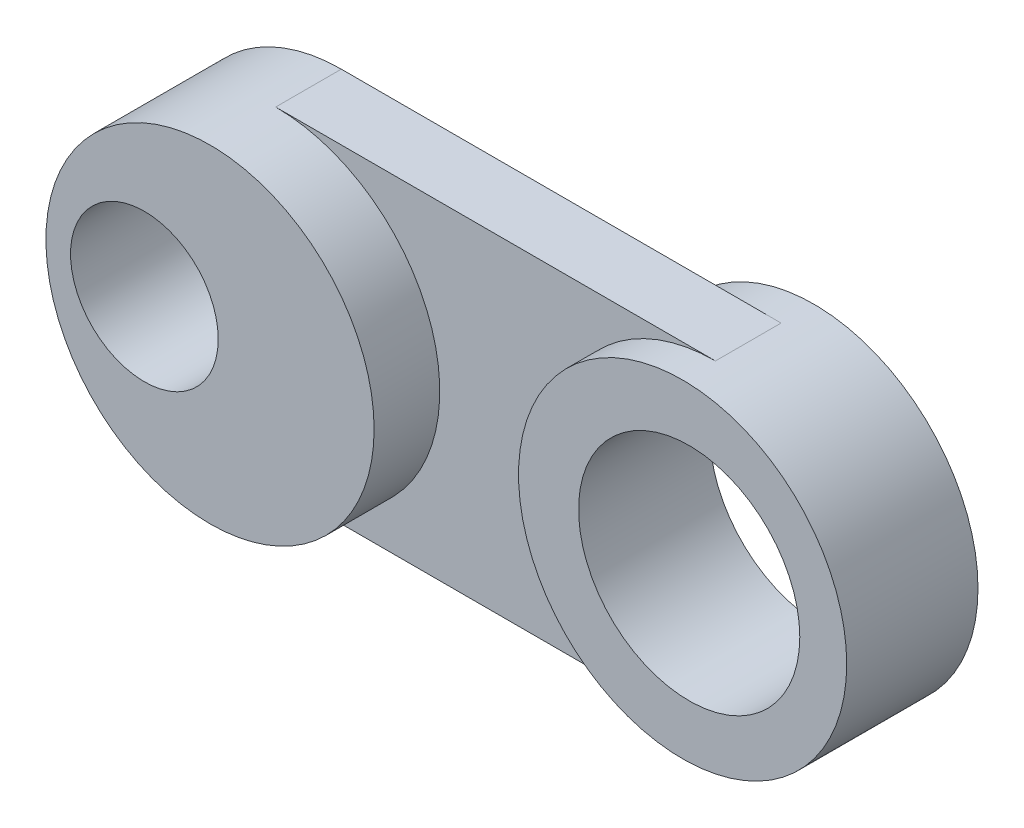
SolidWorks part; units mm, degrees
material "Custom Plastic"
ref_plane "Front Plane" through (0, 0, 0) normal (0, 0, 1) x (1, 0, 0)
ref_plane "Top Plane" through (0, 0, 0) normal (0, 1, 0) x (1, 0, 0)
ref_plane "Right Plane" through (0, 0, 0) normal (1, 0, 0) x (0, 0, -1)
sketch "Sketch1" plane through (0, 0, 0) normal (0, 0, 1) x (1, 0, 0)
  line L0 (0, 12.7) -> (17.018, 12.7)
  line L1 (0, 0) -> (17.018, 0)
  arc A0 (0, 0) -> (0, 12.7) centre (0, 6.35) cw
  arc A1 (17.018, 12.7) -> (17.018, 0) centre (17.018, 6.35) cw
  circle A2 centre (-2.54, 6.35) radius 2.8575
  circle A3 centre (17.272, 6.35) radius 4.2799
  dimension "D1" = 6.35
  dimension "D2" = 17.018
  dimension "D3" = 5.715
  dimension "D4" = 2.54
  dimension "D7" = 8.5598
  dimension "D5" = 0.254
  dimension "D6" = 6.35
extrude "Boss-Extrude1" add sketch "Sketch1" along normal mid plane 2.54
sketch "Sketch2" plane through (0, 0, 1.27) normal (0, 0, 1) x (1, 0, 0)
  circle A0 centre (0, 6.35) radius 6.35
  arc A1 (0, 12.7) -> (0, 0) centre (0, 6.35) ccw construction
  arc M2 (0, 12.7) -> (0, 0) centre (0, 6.35) ccw
  circle M7 centre (-2.54, 6.35) radius 2.8575
extrude "Boss-Extrude2" add sketch "Sketch2" along normal blind 2.54 contours A0 M2 M7
sketch "Sketch4" plane through (0, 0, 0) normal (0, 0, 1) x (1, 0, 0)
  circle A0 centre (17.272, 6.35) radius 4.2799
  circle A1 centre (17.272, 6.35) radius 4.2799 construction
  circle A2 centre (17.018, 6.35) radius 6.35
  arc A3 (17.018, 0) -> (17.018, 12.7) centre (17.018, 6.35) ccw construction
extrude "Boss-Extrude4" add sketch "Sketch4" along normal mid plane 5.08
